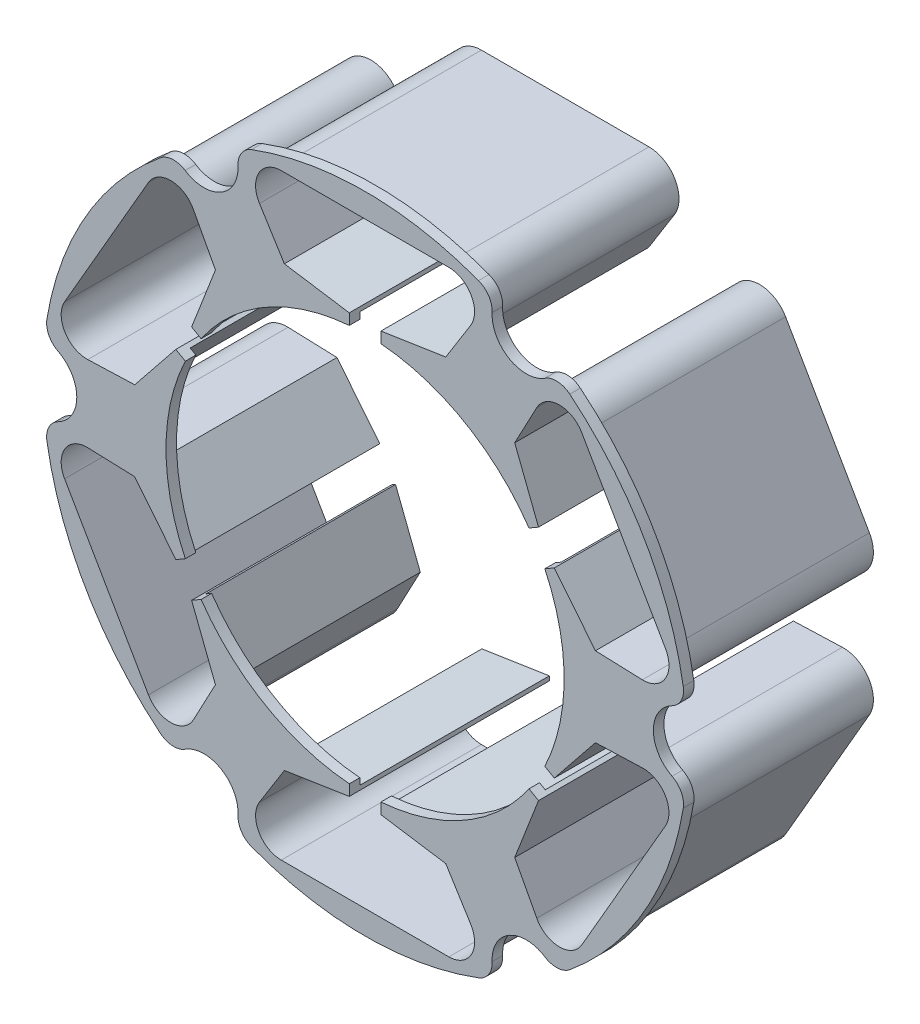
SolidWorks part; units mm, degrees
ref_plane "Ön Düzlem" through (0, 0, 0) normal (0, 0, 1) x (1, 0, 0)
ref_plane "Üst Düzlem" through (0, 0, 0) normal (0, 1, 0) x (1, 0, 0)
ref_plane "Sağ Düzlem" through (0, 0, 0) normal (1, 0, 0) x (0, 0, -1)
sketch "Çizim2" plane through (0, 0, 0) normal (0, 0, 1) x (1, 0, 0)
  line L0 (-1.5, 18.3137) -> (-1.5, 19.3137) construction
  line L13 (1.5, 18.3137) -> (1.5, 19.3137) construction
  line L14 (1.5, 19.3137) -> (8, 20.3137) construction
  line L15 (-1.5, 19.3137) -> (-8, 20.3137) construction
  line L16 (8, 20.3137) -> (10.5, 24.3137) construction
  line L17 (-8, 20.3137) -> (-10.5, 24.3137) construction
  line L18 (-7.956, 28.9037) -> (7.956, 28.9037) construction
  line L20 (-1.5, 19.4654) -> (-7.9092, 20.4515)
  line L21 (-7.9092, 20.4515) -> (-10.3728, 24.3932)
  line L22 (-7.956, 28.7537) -> (7.956, 28.7537)
  line L23 (7.9092, 20.4515) -> (10.3728, 24.3932)
  line L24 (1.5, 19.4654) -> (7.9092, 20.4515)
  line L27 (1.5, 19.8803) -> (7.6612, 20.8281)
  line L28 (7.6612, 20.8281) -> (10.0251, 24.6105)
  line L29 (-7.956, 28.3437) -> (7.956, 28.3437)
  line L30 (-7.6612, 20.8281) -> (-10.0251, 24.6105)
  line L31 (-1.5, 19.8803) -> (-7.6612, 20.8281)
  line L120 (-0.94, 18.3137) -> (-0.94, 19.7941) construction
  line L121 (-1.35, 18.3137) -> (-1.35, 19.4424) construction
  line L122 (1.35, 18.3137) -> (1.35, 19.4424) construction
  line L123 (0.94, 18.3137) -> (0.94, 19.7941) construction
  line L133 (-0.94, 19.7941) -> (-7.6612, 20.8281) construction
  line L134 (0.94, 19.7941) -> (7.6612, 20.8281) construction
  line L145 (-1.5, 19.8803) -> (-1.5, 19.4654)
  line L146 (1.5, 19.8803) -> (1.5, 19.4654)
  line L147 (17.8718, 8.7595) -> (21.8683, 3.7793) [skipped]
  line L148 (21.8683, 3.7793) -> (26.3259, 3.6232) [skipped]
  line L149 (20.5683, 21.0619) -> (28.5243, 7.2817) [skipped]
  line L150 (14.2071, 17.0488) -> (16.3007, 20.9872) [skipped]
  line L151 (16.5218, 11.0977) -> (14.2071, 17.0488) [skipped]
  line L152 (-1.35, 19.4424) -> (-7.9092, 20.4515) construction
  line L153 (16.1626, 10.8903) -> (13.7569, 17.0753) [skipped]
  line L154 (13.7569, 17.0753) -> (15.9387, 21.1797) [skipped]
  line L155 (20.9234, 21.2669) -> (28.8794, 7.4867) [skipped]
  line L156 (21.6661, 3.3761) -> (26.3115, 3.2135) [skipped]
  line L157 (17.5126, 8.552) -> (21.6661, 3.3761) [skipped]
  line L158 (1.35, 19.4424) -> (7.9092, 20.4515) construction
  line L159 (-17.8718, 8.7595) -> (-21.8683, 3.7793) [skipped]
  line L160 (-21.8683, 3.7793) -> (-26.3259, 3.6232) [skipped]
  line L161 (-28.5243, 7.2817) -> (-20.5683, 21.0619) [skipped]
  line L162 (-14.2071, 17.0488) -> (-16.3007, 20.9872) [skipped]
  line L163 (-16.5218, 11.0977) -> (-14.2071, 17.0488) [skipped]
  line L164 (16.4668, 11.2392) -> (14.2071, 17.0488)
  line L165 (-16.1626, 10.8903) -> (-13.7569, 17.0753) [skipped]
  line L166 (-13.7569, 17.0753) -> (-15.9387, 21.1797) [skipped]
  line L167 (-28.8794, 7.4867) -> (-20.9234, 21.2669) [skipped]
  line L168 (-21.6661, 3.3761) -> (-26.3115, 3.2135) [skipped]
  line L169 (-17.5126, 8.552) -> (-21.6661, 3.3761) [skipped]
  line L170 (14.2071, 17.0488) -> (16.3007, 20.9872)
  line L171 (17.5126, -8.552) -> (21.6661, -3.3761) [skipped]
  line L172 (21.6661, -3.3761) -> (26.3115, -3.2135) [skipped]
  line L173 (28.8794, -7.4867) -> (20.9234, -21.2669) [skipped]
  line L174 (13.7569, -17.0753) -> (15.9387, -21.1797) [skipped]
  line L175 (16.1626, -10.8903) -> (13.7569, -17.0753) [skipped]
  line L176 (20.5683, 21.0619) -> (28.5243, 7.2817)
  line L177 (16.5218, -11.0977) -> (14.2071, -17.0488) [skipped]
  line L178 (14.2071, -17.0488) -> (16.3007, -20.9872) [skipped]
  line L179 (28.5243, -7.2817) -> (20.5683, -21.0619) [skipped]
  line L180 (21.8683, -3.7793) -> (26.3259, -3.6232) [skipped]
  line L181 (17.8718, -8.7595) -> (21.8683, -3.7793) [skipped]
  line L182 (21.8683, 3.7793) -> (26.3259, 3.6232)
  line L183 (1.35, -19.4424) -> (7.9092, -20.4515) [skipped]
  line L184 (7.9092, -20.4515) -> (10.3728, -24.3932) [skipped]
  line L185 (7.956, -28.7537) -> (-7.956, -28.7537) [skipped]
  line L186 (-7.9092, -20.4515) -> (-10.3728, -24.3932) [skipped]
  line L187 (-1.35, -19.4424) -> (-7.9092, -20.4515) [skipped]
  line L188 (17.9668, 8.6411) -> (21.8683, 3.7793)
  line L189 (-1.35, -19.8572) -> (-7.6612, -20.8281) [skipped]
  line L190 (-7.6612, -20.8281) -> (-10.0251, -24.6105) [skipped]
  line L191 (7.956, -28.3437) -> (-7.956, -28.3437) [skipped]
  line L192 (7.6612, -20.8281) -> (10.0251, -24.6105) [skipped]
  line L193 (1.35, -19.8572) -> (7.6612, -20.8281) [skipped]
  line L194 (17.9668, 8.6411) -> (17.6076, 8.4337)
  line L195 (-16.1626, -10.8903) -> (-13.7569, -17.0753) [skipped]
  line L196 (-13.7569, -17.0753) -> (-15.9387, -21.1797) [skipped]
  line L197 (-20.9234, -21.2669) -> (-28.8794, -7.4867) [skipped]
  line L198 (-21.6661, -3.3761) -> (-26.3115, -3.2135) [skipped]
  line L199 (-17.5126, -8.552) -> (-21.6661, -3.3761) [skipped]
  line L200 (17.6076, 8.4337) -> (21.6661, 3.3761)
  line L201 (-17.8718, -8.7595) -> (-21.8683, -3.7793) [skipped]
  line L202 (-21.8683, -3.7793) -> (-26.3259, -3.6232) [skipped]
  line L203 (-20.5683, -21.0619) -> (-28.5243, -7.2817) [skipped]
  line L204 (-14.2071, -17.0488) -> (-16.3007, -20.9872) [skipped]
  line L205 (-16.5218, -11.0977) -> (-14.2071, -17.0488) [skipped]
  line L206 (21.6661, 3.3761) -> (26.3115, 3.2135)
  line L207 (20.9234, 21.2669) -> (28.8794, 7.4867)
  line L208 (13.7569, 17.0753) -> (15.9387, 21.1797)
  line L209 (16.1076, 11.0318) -> (13.7569, 17.0753)
  line L210 (16.4668, 11.2392) -> (16.1076, 11.0318)
  line L211 (17.9668, -8.6411) -> (21.8683, -3.7793)
  line L212 (21.8683, -3.7793) -> (26.3259, -3.6232)
  line L213 (28.5243, -7.2817) -> (20.5683, -21.0619)
  line L214 (14.2071, -17.0488) -> (16.3007, -20.9872)
  line L215 (16.4668, -11.2392) -> (14.2071, -17.0488)
  line L216 (16.4668, -11.2392) -> (16.1076, -11.0318)
  line L217 (16.1076, -11.0318) -> (13.7569, -17.0753)
  line L218 (13.7569, -17.0753) -> (15.9387, -21.1797)
  line L219 (28.8794, -7.4867) -> (20.9234, -21.2669)
  line L220 (21.6661, -3.3761) -> (26.3115, -3.2135)
  line L221 (17.6076, -8.4337) -> (21.6661, -3.3761)
  line L222 (17.9668, -8.6411) -> (17.6076, -8.4337)
  line L223 (1.5, -19.8803) -> (7.6612, -20.8281)
  line L224 (7.6612, -20.8281) -> (10.0251, -24.6105)
  line L225 (7.956, -28.3437) -> (-7.956, -28.3437)
  line L226 (-7.6612, -20.8281) -> (-10.0251, -24.6105)
  line L227 (-1.5, -19.8803) -> (-7.6612, -20.8281)
  line L228 (-1.5, -19.8803) -> (-1.5, -19.4654)
  line L229 (-1.5, -19.4654) -> (-7.9092, -20.4515)
  line L230 (-7.9092, -20.4515) -> (-10.3728, -24.3932)
  line L231 (7.956, -28.7537) -> (-7.956, -28.7537)
  line L232 (7.9092, -20.4515) -> (10.3728, -24.3932)
  line L233 (1.5, -19.4654) -> (7.9092, -20.4515)
  line L234 (1.5, -19.8803) -> (1.5, -19.4654)
  line L235 (-16.4668, -11.2392) -> (-14.2071, -17.0488)
  line L236 (-14.2071, -17.0488) -> (-16.3007, -20.9872)
  line L237 (-20.5683, -21.0619) -> (-28.5243, -7.2817)
  line L238 (-21.8683, -3.7793) -> (-26.3259, -3.6232)
  line L239 (-17.9668, -8.6411) -> (-21.8683, -3.7793)
  line L240 (-17.9668, -8.6411) -> (-17.6076, -8.4337)
  line L241 (-17.6076, -8.4337) -> (-21.6661, -3.3761)
  line L242 (-21.6661, -3.3761) -> (-26.3115, -3.2135)
  line L243 (-20.9234, -21.2669) -> (-28.8794, -7.4867)
  line L244 (-13.7569, -17.0753) -> (-15.9387, -21.1797)
  line L245 (-16.1076, -11.0318) -> (-13.7569, -17.0753)
  line L246 (-16.4668, -11.2392) -> (-16.1076, -11.0318)
  line L247 (-17.9668, 8.6411) -> (-21.8683, 3.7793)
  line L248 (-21.8683, 3.7793) -> (-26.3259, 3.6232)
  line L249 (-28.5243, 7.2817) -> (-20.5683, 21.0619)
  line L250 (-14.2071, 17.0488) -> (-16.3007, 20.9872)
  line L251 (-16.4668, 11.2392) -> (-14.2071, 17.0488)
  line L252 (-16.4668, 11.2392) -> (-16.1076, 11.0318)
  line L253 (-16.1076, 11.0318) -> (-13.7569, 17.0753)
  line L254 (-13.7569, 17.0753) -> (-15.9387, 21.1797)
  line L255 (-28.8794, 7.4867) -> (-20.9234, 21.2669)
  line L256 (-21.6661, 3.3761) -> (-26.3115, 3.2135)
  line L257 (-17.6076, 8.4337) -> (-21.6661, 3.3761)
  line L258 (-17.9668, 8.6411) -> (-17.6076, 8.4337)
  circle A0 centre (0, 0) radius 30.62 construction
  arc A1 (-7.956, 28.9037) -> (-10.5, 24.3137) centre (-7.956, 25.9037) ccw construction
  arc A2 (10.5, 24.3137) -> (7.956, 28.9037) centre (7.956, 25.9037) ccw construction
  circle A3 centre (-15.3101, 26.5179) radius 4.3797 construction
  circle A4 centre (-15.3101, 26.5179) radius 1.5 construction
  arc A5 (-7.956, 28.7537) -> (-10.3728, 24.3932) centre (-7.956, 25.9037) ccw
  arc A6 (10.3728, 24.3932) -> (7.956, 28.7537) centre (7.956, 25.9037) ccw
  arc A7 (10.0251, 24.6105) -> (7.956, 28.3437) centre (7.956, 25.9037) ccw
  arc A8 (-7.956, 28.3437) -> (-10.0251, 24.6105) centre (-7.956, 25.9037) ccw
  circle A9 centre (15.3101, 26.5179) radius 1.5 construction
  circle A14 centre (30.6203, 0) radius 1.5 construction
  circle A19 centre (15.3101, -26.5179) radius 1.5 construction
  circle A24 centre (-15.3101, -26.5179) radius 1.5 construction
  circle A29 centre (-30.6203, 0) radius 1.5 construction
  arc A34 (26.3259, 3.6232) -> (28.5243, 7.2817) centre (26.4112, 6.0617) ccw [skipped]
  arc A35 (20.5683, 21.0619) -> (16.3007, 20.9872) centre (18.4552, 19.8419) ccw [skipped]
  arc A36 (20.9234, 21.2669) -> (15.9387, 21.1797) centre (18.4552, 19.8419) ccw [skipped]
  arc A37 (26.3115, 3.2135) -> (28.8794, 7.4867) centre (26.4112, 6.0617) ccw [skipped]
  arc A38 (-28.5243, 7.2817) -> (-26.3259, 3.6232) centre (-26.4112, 6.0617) ccw [skipped]
  arc A39 (-16.3007, 20.9872) -> (-20.5683, 21.0619) centre (-18.4552, 19.8419) ccw [skipped]
  arc A40 (-15.9387, 21.1797) -> (-20.9234, 21.2669) centre (-18.4552, 19.8419) ccw [skipped]
  arc A41 (-28.8794, 7.4867) -> (-26.3115, 3.2135) centre (-26.4112, 6.0617) ccw [skipped]
  arc A42 (28.8794, -7.4867) -> (26.3115, -3.2135) centre (26.4112, -6.0617) ccw [skipped]
  arc A43 (15.9387, -21.1797) -> (20.9234, -21.2669) centre (18.4552, -19.8419) ccw [skipped]
  arc A44 (16.3007, -20.9872) -> (20.5683, -21.0619) centre (18.4552, -19.8419) ccw [skipped]
  arc A45 (28.5243, -7.2817) -> (26.3259, -3.6232) centre (26.4112, -6.0617) ccw [skipped]
  arc A46 (7.956, -28.7537) -> (10.3728, -24.3932) centre (7.956, -25.9037) ccw [skipped]
  arc A47 (-10.3728, -24.3932) -> (-7.956, -28.7537) centre (-7.956, -25.9037) ccw [skipped]
  arc A48 (-10.0251, -24.6105) -> (-7.956, -28.3437) centre (-7.956, -25.9037) ccw [skipped]
  arc A49 (7.956, -28.3437) -> (10.0251, -24.6105) centre (7.956, -25.9037) ccw [skipped]
  arc A50 (-20.9234, -21.2669) -> (-15.9387, -21.1797) centre (-18.4552, -19.8419) ccw [skipped]
  arc A51 (-26.3115, -3.2135) -> (-28.8794, -7.4867) centre (-26.4112, -6.0617) ccw [skipped]
  arc A52 (-26.3259, -3.6232) -> (-28.5243, -7.2817) centre (-26.4112, -6.0617) ccw [skipped]
  arc A53 (-20.5683, -21.0619) -> (-16.3007, -20.9872) centre (-18.4552, -19.8419) ccw [skipped]
  arc A54 (20.5683, 21.0619) -> (16.3007, 20.9872) centre (18.4552, 19.8419) ccw
  arc A55 (26.3259, 3.6232) -> (28.5243, 7.2817) centre (26.4112, 6.0617) ccw
  arc A56 (26.3115, 3.2135) -> (28.8794, 7.4867) centre (26.4112, 6.0617) ccw
  arc A57 (20.9234, 21.2669) -> (15.9387, 21.1797) centre (18.4552, 19.8419) ccw
  arc A58 (28.5243, -7.2817) -> (26.3259, -3.6232) centre (26.4112, -6.0617) ccw
  arc A59 (16.3007, -20.9872) -> (20.5683, -21.0619) centre (18.4552, -19.8419) ccw
  arc A60 (15.9387, -21.1797) -> (20.9234, -21.2669) centre (18.4552, -19.8419) ccw
  arc A61 (28.8794, -7.4867) -> (26.3115, -3.2135) centre (26.4112, -6.0617) ccw
  arc A62 (7.956, -28.3437) -> (10.0251, -24.6105) centre (7.956, -25.9037) ccw
  arc A63 (-10.0251, -24.6105) -> (-7.956, -28.3437) centre (-7.956, -25.9037) ccw
  arc A64 (-10.3728, -24.3932) -> (-7.956, -28.7537) centre (-7.956, -25.9037) ccw
  arc A65 (7.956, -28.7537) -> (10.3728, -24.3932) centre (7.956, -25.9037) ccw
  arc A66 (-20.5683, -21.0619) -> (-16.3007, -20.9872) centre (-18.4552, -19.8419) ccw
  arc A67 (-26.3259, -3.6232) -> (-28.5243, -7.2817) centre (-26.4112, -6.0617) ccw
  arc A68 (-26.3115, -3.2135) -> (-28.8794, -7.4867) centre (-26.4112, -6.0617) ccw
  arc A69 (-20.9234, -21.2669) -> (-15.9387, -21.1797) centre (-18.4552, -19.8419) ccw
  arc A70 (-28.5243, 7.2817) -> (-26.3259, 3.6232) centre (-26.4112, 6.0617) ccw
  arc A71 (-16.3007, 20.9872) -> (-20.5683, 21.0619) centre (-18.4552, 19.8419) ccw
  arc A72 (-15.9387, 21.1797) -> (-20.9234, 21.2669) centre (-18.4552, 19.8419) ccw
  arc A73 (-28.8794, 7.4867) -> (-26.3115, 3.2135) centre (-26.4112, 6.0617) ccw
  point P48 (18.7648, 8.7352)
  point P49 (0, 0)
  point P159 (0, 0)
  point P176 (0, 0)
  point P189 (0, 0)
  dimension "D1" = 61.24
  dimension "D8" = 3
  dimension "D9" = 3
  dimension "D10" = 3
  dimension "D11" = 7.3541
  dimension "D12" = 4.8101
  dimension "D14" = 15.912
  dimension "D2" = 4
  dimension "D3" = 4
  dimension "D4" = 6.5
  dimension "D5" = 6.5
  dimension "D6" = 1
  dimension "D7" = 1
  dimension "D13" = 2.2043
  dimension "D15" = 3
  dimension "D16" = 1
  dimension "D17" = 1
  dimension "D18" = 21
  dimension "D19" = 1.5
  dimension "D20" = 18.375
  dimension "D24" = 6
  dimension "D25" = 3
  dimension "D26" = 1.5
  dimension "D21" = 0.15
  dimension "D22" = 0.41
  dimension "D23" = 6
extrude "Yükseklik-Ekstrüzyon1" add sketch "Çizim2" along normal blind 18
sketch "Çizim3" plane through (0, 0, 18) normal (0, 0, 1) x (1, 0, 0)
  line L71 (10.0251, 24.6105) -> (7.6612, 20.8281) construction
  line L72 (7.6612, 20.8281) -> (1.5, 19.8803) construction
  line L73 (-7.956, 28.3437) -> (7.956, 28.3437) construction
  line L74 (-1.5, 19.8803) -> (-7.6612, 20.8281) construction
  line L75 (-7.6612, 20.8281) -> (-10.0251, 24.6105) construction
  line L76 (10.0251, 24.6105) -> (7.6612, 20.8281)
  line L77 (7.6612, 20.8281) -> (1.5, 19.8803)
  line L78 (-7.956, 28.3437) -> (7.956, 28.3437)
  line L79 (-1.5, 19.8803) -> (-7.6612, 20.8281)
  line L80 (-7.6612, 20.8281) -> (-10.0251, 24.6105)
  line L81 (-1.5, 19.8803) -> (-1.5, 18.8404)
  line L82 (1.5, 19.8803) -> (1.5, 18.8404)
  line L83 (17.9668, 8.6411) -> (17.0662, 8.1212)
  line L84 (21.8683, 3.7793) -> (17.9668, 8.6411)
  line L85 (26.3259, 3.6232) -> (21.8683, 3.7793)
  line L86 (20.5683, 21.0619) -> (28.5243, 7.2817)
  line L87 (14.2071, 17.0488) -> (16.3007, 20.9872)
  line L88 (16.4668, 11.2392) -> (14.2071, 17.0488)
  line L89 (16.4668, 11.2392) -> (15.5662, 10.7192)
  line L90 (16.4668, -11.2392) -> (15.5662, -10.7192)
  line L91 (14.2071, -17.0488) -> (16.4668, -11.2392)
  line L92 (16.3007, -20.9872) -> (14.2071, -17.0488)
  line L93 (28.5243, -7.2817) -> (20.5683, -21.0619)
  line L94 (21.8683, -3.7793) -> (26.3259, -3.6232)
  line L95 (17.9668, -8.6411) -> (21.8683, -3.7793)
  line L96 (17.9668, -8.6411) -> (17.0662, -8.1212)
  line L97 (-1.5, -19.8803) -> (-1.5, -18.8404)
  line L98 (-7.6612, -20.8281) -> (-1.5, -19.8803)
  line L99 (-10.0251, -24.6105) -> (-7.6612, -20.8281)
  line L100 (7.956, -28.3437) -> (-7.956, -28.3437)
  line L101 (7.6612, -20.8281) -> (10.0251, -24.6105)
  line L102 (1.5, -19.8803) -> (7.6612, -20.8281)
  line L103 (1.5, -19.8803) -> (1.5, -18.8404)
  line L104 (-17.9668, -8.6411) -> (-17.0662, -8.1212)
  line L105 (-21.8683, -3.7793) -> (-17.9668, -8.6411)
  line L106 (-26.3259, -3.6232) -> (-21.8683, -3.7793)
  line L107 (-20.5683, -21.0619) -> (-28.5243, -7.2817)
  line L108 (-14.2071, -17.0488) -> (-16.3007, -20.9872)
  line L109 (-16.4668, -11.2392) -> (-14.2071, -17.0488)
  line L110 (-16.4668, -11.2392) -> (-15.5662, -10.7192)
  line L111 (-16.4668, 11.2392) -> (-15.5662, 10.7192)
  line L112 (-14.2071, 17.0488) -> (-16.4668, 11.2392)
  line L113 (-16.3007, 20.9872) -> (-14.2071, 17.0488)
  line L114 (-28.5243, 7.2817) -> (-20.5683, 21.0619)
  line L115 (-21.8683, 3.7793) -> (-26.3259, 3.6232)
  line L116 (-17.9668, 8.6411) -> (-21.8683, 3.7793)
  line L117 (-17.9668, 8.6411) -> (-17.0662, 8.1212)
  arc A0 (-18.0344, 24.7456) -> (-30.4475, 3.2454) centre (0, 0) ccw
  circle A1 centre (-15.31, 26.5177) radius 4.5296 construction
  arc A3 (-7.956, 28.7537) -> (-10.3728, 24.3932) centre (-7.956, 25.9037) ccw construction
  arc A4 (-18.0344, 24.7456) -> (-12.4131, 27.991) centre (-15.31, 26.5177) ccw
  arc A5 (12.4131, 27.991) -> (18.0344, 24.7456) centre (15.31, 26.5177) ccw
  arc A6 (30.4475, 3.2454) -> (30.4475, -3.2454) centre (30.62, 0) ccw
  arc A7 (18.0344, -24.7456) -> (12.4131, -27.991) centre (15.31, -26.5177) ccw
  arc A8 (-12.4131, -27.991) -> (-18.0344, -24.7456) centre (-15.31, -26.5177) ccw
  arc A9 (-30.4475, -3.2454) -> (-30.4475, 3.2454) centre (-30.62, 0) ccw
  arc A10 (12.4131, 27.991) -> (-12.4131, 27.991) centre (0, 0) ccw
  arc A11 (30.4475, 3.2454) -> (18.0344, 24.7456) centre (0, 0) ccw
  arc A12 (18.0344, -24.7456) -> (30.4475, -3.2454) centre (0, 0) ccw
  arc A13 (-12.4131, -27.991) -> (12.4131, -27.991) centre (0, 0) ccw
  arc A14 (-30.4475, -3.2454) -> (-18.0344, -24.7456) centre (0, 0) ccw
  arc A35 (-1.5, 18.8404) -> (-15.5662, 10.7192) centre (0, 0) ccw
  arc A36 (10.0251, 24.6105) -> (7.956, 28.3437) centre (7.956, 25.9037) ccw construction
  arc A37 (-7.956, 28.3437) -> (-10.0251, 24.6105) centre (-7.956, 25.9037) ccw construction
  arc A38 (10.0251, 24.6105) -> (7.956, 28.3437) centre (7.956, 25.9037) ccw
  arc A39 (-7.956, 28.3437) -> (-10.0251, 24.6105) centre (-7.956, 25.9037) ccw
  arc A40 (26.3259, 3.6232) -> (28.5243, 7.2817) centre (26.4112, 6.0617) ccw
  arc A41 (20.5683, 21.0619) -> (16.3007, 20.9872) centre (18.4552, 19.8419) ccw
  arc A42 (16.3007, -20.9872) -> (20.5683, -21.0619) centre (18.4552, -19.8419) ccw
  arc A43 (28.5243, -7.2817) -> (26.3259, -3.6232) centre (26.4112, -6.0617) ccw
  arc A44 (-10.0251, -24.6105) -> (-7.956, -28.3437) centre (-7.956, -25.9037) ccw
  arc A45 (7.956, -28.3437) -> (10.0251, -24.6105) centre (7.956, -25.9037) ccw
  arc A46 (-26.3259, -3.6232) -> (-28.5243, -7.2817) centre (-26.4112, -6.0617) ccw
  arc A47 (-20.5683, -21.0619) -> (-16.3007, -20.9872) centre (-18.4552, -19.8419) ccw
  arc A48 (-16.3007, 20.9872) -> (-20.5683, 21.0619) centre (-18.4552, 19.8419) ccw
  arc A49 (-28.5243, 7.2817) -> (-26.3259, 3.6232) centre (-26.4112, 6.0617) ccw
  arc A50 (15.5662, 10.7192) -> (1.5, 18.8404) centre (0, 0) ccw
  arc A51 (17.0662, -8.1212) -> (17.0662, 8.1212) centre (0, 0) ccw
  arc A52 (1.5, -18.8404) -> (15.5662, -10.7192) centre (0, 0) ccw
  arc A53 (-15.5662, -10.7192) -> (-1.5, -18.8404) centre (0, 0) ccw
  arc A54 (-17.0662, 8.1212) -> (-17.0662, -8.1212) centre (0, 0) ccw
  arc A55 (-15.9387, 21.1797) -> (-20.9234, 21.2669) centre (-18.4552, 19.8419) ccw construction
  point P1 (20.4714, 8.1472)
  point P5 (-14.5747, 26.9288)
  point P30 (0, 0)
  point P43 (0, 0)
  point P102 (0, 0)
  point P103 (0, 0)
  point P104 (0, 0)
  point P141 (0, 0)
  dimension "D1" = 61.24
  dimension "D2" = 6.5
  dimension "D4" = 37.8
  dimension "D3" = 6
  dimension "D5" = 6
extrude "Yükseklik-Ekstrüzyon2" add sketch "Çizim3" along normal blind 1
fillet "Radyus2" radius 2 12 edges at (18.0344, 24.7456, 18.5) (12.4131, 27.991, 18.5) (30.4475, 3.2454, 18.5) (30.4475, -3.2454, 18.5) (12.4131, -27.991, 18.5) (18.0344, -24.7456, 18.5) (-12.4131, -27.991, 18.5) (-18.0344, -24.7456, 18.5) (-30.4475, -3.2454, 18.5) (-30.4475, 3.2454, 18.5) (-12.4131, 27.991, 18.5) (-18.0344, 24.7456, 18.5)
